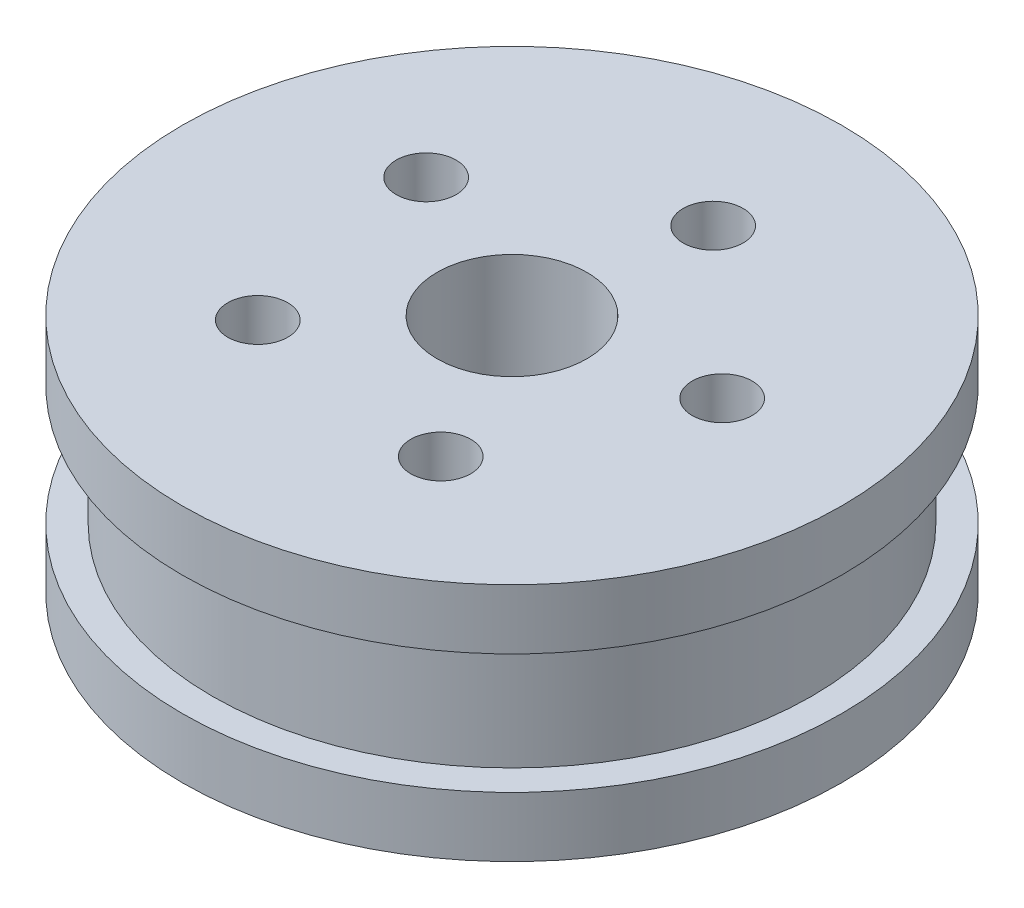
SolidWorks part; units mm, degrees
ref_plane "Front Plane" through (0, 0, 0) normal (0, 0, 1) x (1, 0, 0)
ref_plane "Top Plane" through (0, 0, 0) normal (0, 1, 0) x (1, 0, 0)
ref_plane "Right Plane" through (0, 0, 0) normal (1, 0, 0) x (0, 0, -1)
sketch "Sketch1" plane through (0, 0, 0) normal (0, 0, 1) x (1, 0, 0)
  line L0 (0, 0) -> (0, 2.54)
  line L4 (0, -7.62) -> (0, -5.08)
  line L5 (0, -5.08) -> (1.27, -5.08)
  line L6 (1.27, -5.08) -> (1.27, 0)
  line L7 (1.27, 0) -> (0, 0)
  line L8 (0, -7.62) -> (13.97, -7.62)
  line L9 (13.97, -7.62) -> (13.97, 2.54)
  line L10 (13.97, 2.54) -> (0, 2.54)
  dimension "D1" = 5.08
  dimension "D2" = 13.97
  dimension "D3" = 1.27
  dimension "D4" = 5.08
  dimension "D5" = 2.54
  dimension "D6" = 2.54
revolve "Revolve1" add sketch "Sketch1" angle 360 about L9
sketch "Sketch4" plane through (0, 2.54, 0) normal (0, 1, 0) x (1, 0, 0)
  circle A1 centre (13.97, 0) radius 3.175
  dimension "D1" = 6.35
extrude "Cut-Extrude3" cut sketch "Sketch4" against normal through all
sketch "Sketch5" plane through (0, 2.54, 0) normal (0, 1, 0) x (1, 0, 0)
sketch "Sketch6" plane through (0, 2.54, 0) normal (0, 1, 0) x (1, 0, 0)
  circle A1 centre (7.0793, 3.2531) radius 1.27
  circle A2 centre (14.9346, 7.5587) radius 1.27
  circle A3 centre (21.4568, 1.4184) radius 1.27
  circle A4 centre (17.6326, -6.6821) radius 1.27
  circle A5 centre (8.7468, -5.5482) radius 1.27
  point P14 (13.97, 0)
  dimension "D1" = 5
  dimension "D2" = 2.54
extrude "Cut-Extrude5" cut sketch "Sketch6" against normal through all
